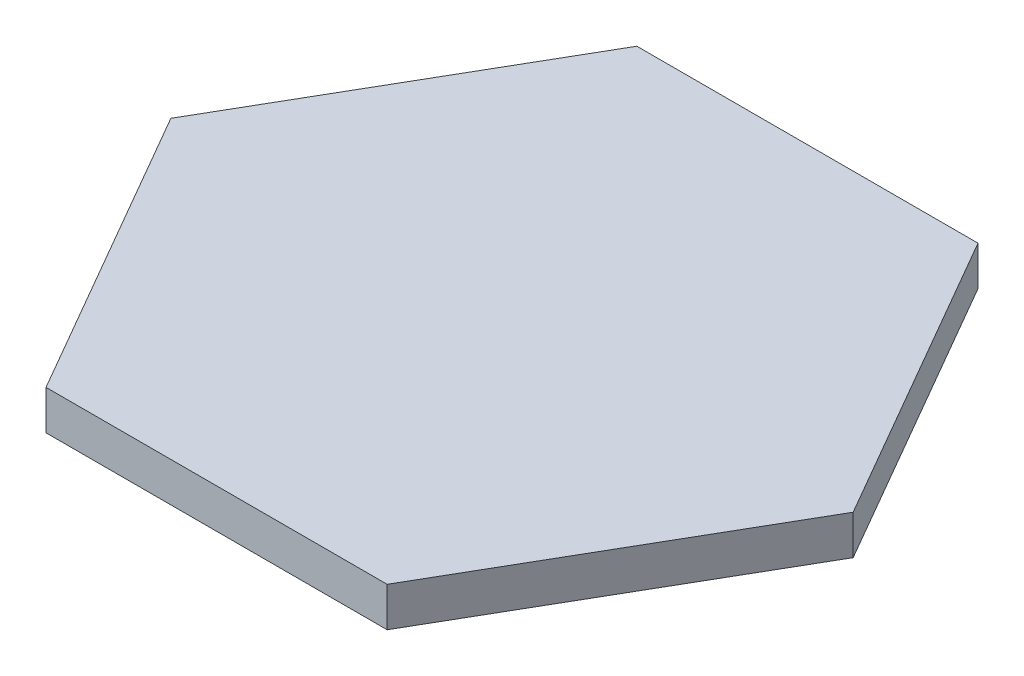
SolidWorks part; units mm, degrees
ref_plane "Front Plane" through (0, 0, 0) normal (0, 0, 1) x (1, 0, 0)
ref_plane "Top Plane" through (0, 0, 0) normal (0, 1, 0) x (1, 0, 0)
ref_plane "Right Plane" through (0, 0, 0) normal (1, 0, 0) x (0, 0, -1)
sketch "Sketch1" plane through (0, 0, 0) normal (0, 1, 0) x (1, 0, 0)
  line L1 (34.641, 0) -> (17.3205, 30)
  line L2 (17.3205, 30) -> (-17.3205, 30)
  line L3 (-17.3205, 30) -> (-34.641, 0)
  line L4 (-34.641, 0) -> (-17.3205, -30)
  line L5 (-17.3205, -30) -> (17.3205, -30)
  line L6 (17.3205, -30) -> (34.641, 0)
  circle A0 centre (0, 0) radius 30 construction
  dimension "D1" = 30
extrude "Boss-Extrude1" add sketch "Sketch1" along normal blind 4
